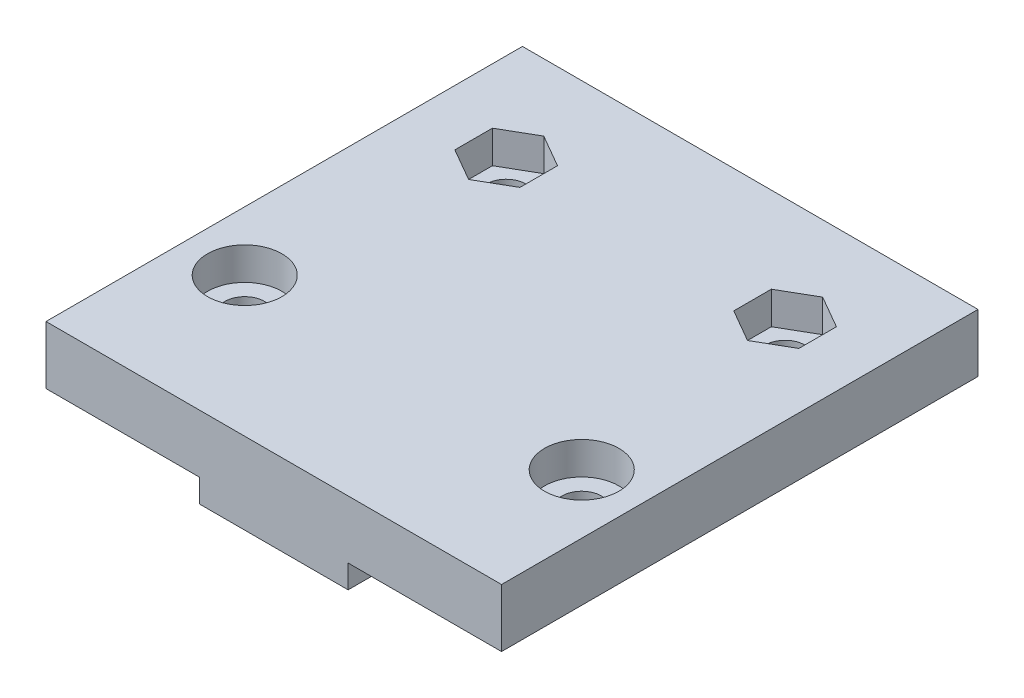
SolidWorks part; units mm, degrees
ref_plane "Спереди" through (0, 0, 0) normal (0, 0, 1) x (1, 0, 0)
ref_plane "Сверху" through (0, 0, 0) normal (0, 1, 0) x (1, 0, 0)
ref_plane "Справа" through (0, 0, 0) normal (1, 0, 0) x (0, 0, -1)
sketch "Эскиз1" plane through (0, 0, 0) normal (0, 0, 1) x (1, 0, 0)
  line L1 (20, -10) -> (-20, -10)
  line L2 (20, -10) -> (20, 10)
  line L3 (20, 10) -> (-20, 10)
  line L4 (-20, -10) -> (-20, 10)
  line L5 (20, -10) -> (-20, 10) construction
  line L6 (20, 10) -> (-20, -10) construction
  point P0 (0, 0)
  dimension "D1" = 40
  dimension "D2" = 20
extrude "Бобышка-Вытянуть1" add sketch "Эскиз1" along normal blind 6
sketch "Эскиз2" plane through (0, 0, 0) normal (0, 0, -1) x (-1, 0, 0)
  line L0 (20, -10) -> (-20, -10) construction
  line L1 (20, 22.5) -> (-20, 22.5)
  line L2 (20, 22.5) -> (20, -10)
  line L3 (20, -10) -> (-20, -10)
  line L4 (-20, 22.5) -> (-20, -10)
  line L5 (20, 22.5) -> (-20, -10) construction
  line L6 (20, -10) -> (-20, 22.5) construction
  line L7 (-20, -10) -> (-20, 10) construction
  point P0 (0, 6.25)
  dimension "D1" = 22.5
extrude "Бобышка-Вытянуть2" add sketch "Эскиз2" along normal blind 35
sketch "Эскиз3" plane through (0, -10, 0) normal (0, -1, 0) x (1, 0, 0)
  line L0 (0, 6) -> (0, -35) construction
  line L1 (-20, 6) -> (20, 6) construction
  line L2 (20, -35) -> (-20, -35) construction
  line L3 (-7, 6) -> (-7, -1)
  line L4 (-7, -1) -> (-9, -1)
  line L5 (-9, -1) -> (-9, -23)
  line L6 (-9, -23) -> (-6.5, -26)
  line L7 (-6.5, -26) -> (-6.5, -33)
  line L8 (-6.5, -33) -> (-4.5, -33)
  line L9 (-4.5, -33) -> (-4.5, -35)
  line L10 (4.5, -33) -> (4.5, -35)
  line L11 (6.5, -33) -> (4.5, -33)
  line L12 (6.5, -26) -> (6.5, -33)
  line L13 (9, -23) -> (6.5, -26)
  line L14 (9, -1) -> (9, -23)
  line L15 (7, -1) -> (9, -1)
  line L16 (7, 6) -> (7, -1)
  line L17 (-7, 6) -> (7, 6)
  line L18 (4.5, -35) -> (-4.5, -35)
  dimension "D1" = 7
  dimension "D2" = 9
  dimension "D3" = 6.5
  dimension "D4" = 4.5
  dimension "D5" = 7
  dimension "D6" = 22
  dimension "D7" = 25
  dimension "D8" = 32
extrude "Вырез-Вытянуть1" cut sketch "Эскиз3" against normal blind 13
sketch "Эскиз5" plane through (0, 3, 0) normal (0, -1, 0) x (1, 0, 0)
  line L0 (-9, -1) -> (9, -1)
  line L1 (9, -1) -> (9, -23)
  line L2 (9, -23) -> (6.5, -26)
  line L3 (6.5, -26) -> (6.5, -33)
  line L4 (6.5, -33) -> (-6.5, -33)
  line L5 (-6.5, -33) -> (-6.5, -26)
  line L6 (-6.5, -26) -> (-9, -23)
  line L7 (-9, -23) -> (-9, -1)
extrude "Вырез-Вытянуть2" cut sketch "Эскиз5" against normal blind 2
sketch "Эскиз6" plane through (0, -10, 0) normal (0, -1, 0) x (1, 0, 0)
  line L0 (20, 6) -> (20, -35) construction
  line L1 (-20, -35) -> (20, -35)
  line L2 (-20, -35) -> (-20, 6)
  line L3 (-20, 6) -> (20, 6)
  line L4 (20, -35) -> (20, 6)
  line L6 (-20, 6) -> (-7, 6) construction
extrude "Вырез-Вытянуть3" cut sketch "Эскиз6" against normal blind 5
sketch "Эскиз8" plane through (0, -5, 0) normal (0, -1, 0) x (1, 0, 0)
  line L0 (0, 6) -> (0, -35) construction
  line L1 (7, 6) -> (-7, 6) construction
  line L2 (-4.5, -35) -> (4.5, -35) construction
  line L3 (9, -6) -> (20, -6) construction
  line L4 (9, -23) -> (9, -1) construction
  line L5 (20, -35) -> (20, 6) construction
  line L6 (20, 6) -> (7, 6) construction
  circle A0 centre (12, -26) radius 1.7
  circle A1 centre (14.5, -6) radius 1.7
  circle A2 centre (-12, -26) radius 1.7
  circle A3 centre (-14.5, -6) radius 1.7
  dimension "D1" = 12
  dimension "D2" = 3.4
  dimension "D4" = 3.4
  dimension "D3" = 12
extrude "Вырез-Вытянуть4" cut sketch "Эскиз8" against normal through all
sketch "Эскиз9" plane through (0, 0, 6) normal (0, 0, 1) x (1, 0, 0)
  line L0 (20, -5) -> (20, 10) construction
  line L1 (-20, 10) -> (20, 10)
  line L2 (-20, 10) -> (-20, 22.5)
  line L3 (-20, 22.5) -> (20, 22.5)
  line L4 (20, 10) -> (20, 22.5)
  line L5 (-20, -5) -> (20, -5)
  line L6 (-20, -5) -> (-20, 3)
  line L7 (-20, 3) -> (20, 3)
  line L8 (20, -5) -> (20, 3)
  line L9 (7, 3) -> (-7, 3) construction
extrude "Вырез-Вытянуть5" cut sketch "Эскиз9" against normal up to surface (41 mm away) up to face at (0, 3.875, -35)
sketch "Эскиз10" plane through (0, 3, 0) normal (0, -1, 0) x (1, 0, 0)
  line L0 (0, 6) -> (0, -35) construction
  line L1 (20, 6) -> (-20, 6) construction
  line L2 (-20, -35) -> (20, -35) construction
  line L3 (-20, 6) -> (-6.4, 6)
  line L4 (-6.4, 6) -> (-6.4, -1)
  line L5 (-9, -1) -> (9, -1) construction
  line L6 (-6.4, -1) -> (-4, -33)
  line L7 (6.5, -33) -> (-6.5, -33) construction
  line L8 (-4, -33) -> (-4, -35)
  line L9 (-4, -35) -> (-20, -35)
  line L10 (-20, -35) -> (-20, 6)
  dimension "D1" = 4
  dimension "D2" = 6.4
extrude "Вырез-Вытянуть6" cut sketch "Эскиз10" against normal up to surface (2 mm away) up to face at (0, 5, -20.75)
mirror "Зеркальное отражение1" about plane through (0, 0, 0) normal (1, 0, 0) of "Вырез-Вытянуть6"
sketch "Эскиз11" plane through (0, 10, 0) normal (0, 1, 0) x (1, 0, 0)
  line L0 (0, 35) -> (0, -6) construction
  line L1 (-12, 29.2332) -> (-14.8, 27.6166)
  line L2 (-14.8, 27.6166) -> (-14.8, 24.3834)
  line L3 (-14.8, 24.3834) -> (-12, 22.7668)
  line L4 (-12, 22.7668) -> (-9.2, 24.3834)
  line L5 (-9.2, 24.3834) -> (-9.2, 27.6166)
  line L6 (-9.2, 27.6166) -> (-12, 29.2332)
  line L7 (20, 35) -> (-20, 35) construction
  line L8 (20, -6) -> (-20, -6) construction
  line L9 (9.2, 27.6166) -> (12, 29.2332)
  line L10 (9.2, 24.3834) -> (9.2, 27.6166)
  line L11 (12, 22.7668) -> (9.2, 24.3834)
  line L12 (14.8, 24.3834) -> (12, 22.7668)
  line L13 (14.8, 27.6166) -> (14.8, 24.3834)
  line L14 (12, 29.2332) -> (14.8, 27.6166)
  circle A0 centre (-12, 26) radius 2.8 construction
  circle A1 centre (12, 26) radius 2.8 construction
  circle A2 centre (14.5, 6) radius 3.2
  circle A3 centre (-14.5, 6) radius 3.2
  dimension "D1" = 5.6
  dimension "D2" = 6.4
extrude "Вырез-Вытянуть7" cut sketch "Эскиз11" against normal blind 2.8
sketch "Эскиз12" plane through (0, 10, 0) normal (0, 1, 0) x (1, 0, 0)
  line L0 (0, 35) -> (0, -6) construction
  line L1 (20, 35) -> (-20, 35) construction
  line L2 (20, -6) -> (-20, -6) construction
  line L3 (-20, -6) -> (-20, 35) construction
  line L4 (-19.6, 35) -> (-20, 35)
  line L5 (-19.6, 35) -> (-19.6, -6)
  line L6 (-19.6, -6) -> (-20, -6)
  line L7 (-20, 35) -> (-20, -6)
  line L8 (20, 35) -> (20, -6)
  line L9 (19.6, -6) -> (20, -6)
  line L10 (19.6, 35) -> (19.6, -6)
  line L11 (19.6, 35) -> (20, 35)
  dimension "D1" = 0.4
extrude "Вырез-Вытянуть8" cut sketch "Эскиз12" against normal up to surface (5 mm away) up to face at (0, 5, -15.3333)
